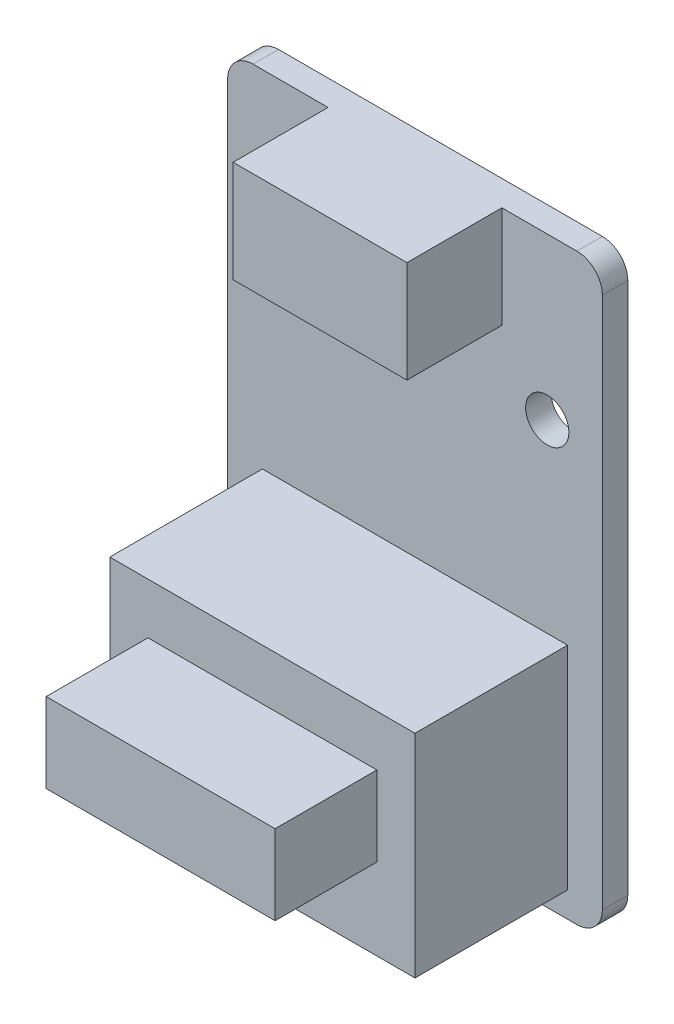
SolidWorks part; units mm, degrees
ref_plane "前基準面" through (0, 0, 0) normal (0, 0, 1) x (1, 0, 0)
ref_plane "上基準面" through (0, 0, 0) normal (0, 1, 0) x (1, 0, 0)
ref_plane "右基準面" through (0, 0, 0) normal (1, 0, 0) x (0, 0, -1)
sketch "草圖1" plane through (0, 0, 0) normal (0, 0, 1) x (1, 0, 0)
  line L1 (-6.7606, -58.7442) -> (12.3394, -58.7442)
  line L2 (-8.2606, -60.2442) -> (-8.2606, -91.6442)
  line L3 (-6.7606, -93.1442) -> (12.3394, -93.1442)
  line L4 (13.8394, -60.2442) -> (13.8394, -91.6442)
  arc A0 (12.3394, -93.1442) -> (13.8394, -91.6442) centre (12.3394, -91.6442) ccw
  arc A1 (-8.2606, -91.6442) -> (-6.7606, -93.1442) centre (-6.7606, -91.6442) ccw
  arc A2 (-6.7606, -58.7442) -> (-8.2606, -60.2442) centre (-6.7606, -60.2442) ccw
  arc A3 (12.3394, -58.7442) -> (13.8394, -60.2442) centre (12.3394, -60.2442) cw
  point P8 (-8.2606, -93.1442)
  point P11 (-8.2606, -58.7442)
  point P14 (13.8394, -58.7442)
  dimension "D3" = 1.5
  dimension "D1" = 22.1
  dimension "D2" = 34.4
extrude "填料-伸長1" add sketch "草圖1" along normal blind 1.5
sketch "草圖2" plane through (0, 0, 1.5) normal (0, 0, 1) x (1, 0, 0)
  line L0 (-6.7606, -93.1442) -> (12.3394, -93.1442) construction
  line L1 (-6.2106, -79.1442) -> (11.7894, -79.1442)
  line L2 (-6.2106, -79.1442) -> (-6.2106, -91.6442)
  line L3 (-6.2106, -91.6442) -> (11.7894, -91.6442)
  line L4 (11.7894, -79.1442) -> (11.7894, -91.6442)
  point P6 (2.7894, -93.1442)
  point P7 (2.7894, -91.6442)
  dimension "D1" = 18
  dimension "D2" = 12.5
  dimension "D3" = 1.5
extrude "填料-伸長2" add sketch "草圖2" along normal blind 9
sketch "草圖3" plane through (0, 0, 10.5) normal (0, 0, 1) x (1, 0, 0)
  line L0 (-6.2106, -91.6442) -> (11.7894, -91.6442) construction
  line L1 (-3.9606, -82.1442) -> (9.5394, -82.1442)
  line L2 (-3.9606, -82.1442) -> (-3.9606, -86.8442)
  line L3 (-3.9606, -86.8442) -> (9.5394, -86.8442)
  line L4 (9.5394, -82.1442) -> (9.5394, -86.8442)
  line L5 (11.7894, -79.1442) -> (-6.2106, -79.1442) construction
  point P4 (2.7894, -86.8442)
  point P7 (2.7894, -91.6442)
  dimension "D1" = 3
extrude "填料-伸長3" add sketch "草圖3" along normal blind 6
sketch "草圖4" plane through (0, 0, 1.5) normal (0, 0, 1) x (1, 0, 0)
  line L0 (12.3394, -58.7442) -> (-6.7606, -58.7442) construction
  line L1 (-2.3356, -58.7442) -> (7.9144, -58.7442)
  line L2 (-2.3356, -58.7442) -> (-2.3356, -64.7442)
  line L3 (-2.3356, -64.7442) -> (7.9144, -64.7442)
  line L4 (7.9144, -58.7442) -> (7.9144, -64.7442)
  point P6 (2.7894, -58.7442)
  point P7 (2.7894, -58.7442)
  dimension "D1" = 10.25
  dimension "D2" = 6
extrude "填料-伸長4" add sketch "草圖4" along normal blind 5.6
hole_wizard "M2.5 螺旋的螺孔鑽1" positions "草圖5" profile "草圖6" hole size "M2.5x0.45" standard "Ansi Metric" end condition through all
sketch "草圖5" plane through (0, 0, 1.5) normal (0, 0, 1) x (1, 0, 0)
  line L0 (-8.2606, -60.2442) -> (-8.2606, -91.6442) construction
  line L1 (13.8394, -91.6442) -> (13.8394, -60.2442) construction
  line L2 (12.3394, -58.7442) -> (7.9144, -58.7442) construction
  line L3 (-2.3356, -58.7442) -> (-6.7606, -58.7442) construction
  point P0 (-5.0106, -68.2442)
  point P2 (10.5894, -68.2442)
  dimension "D1" = 3.25
  dimension "D2" = 3.25
  dimension "D3" = 9.5
  dimension "D4" = 9.5
sketch "草圖6" plane through (-5.0106, -68.2442, 1.5) normal (1, 0, 0) x (0, -1, 0)
  line L0 (0, 0) -> (0, 1.5)
  line L1 (0, 1.5) -> (1.275, 1.5)
  line L2 (1.275, 1.5) -> (1.275, 0)
  line L5 (1.275, 0) -> (0, 0)
  line L11 (0, -6.35) -> (0, 107.95) construction
  dimension "貫穿孔直徑" = 2.55
  dimension "貫穿孔深度" = 1.5
